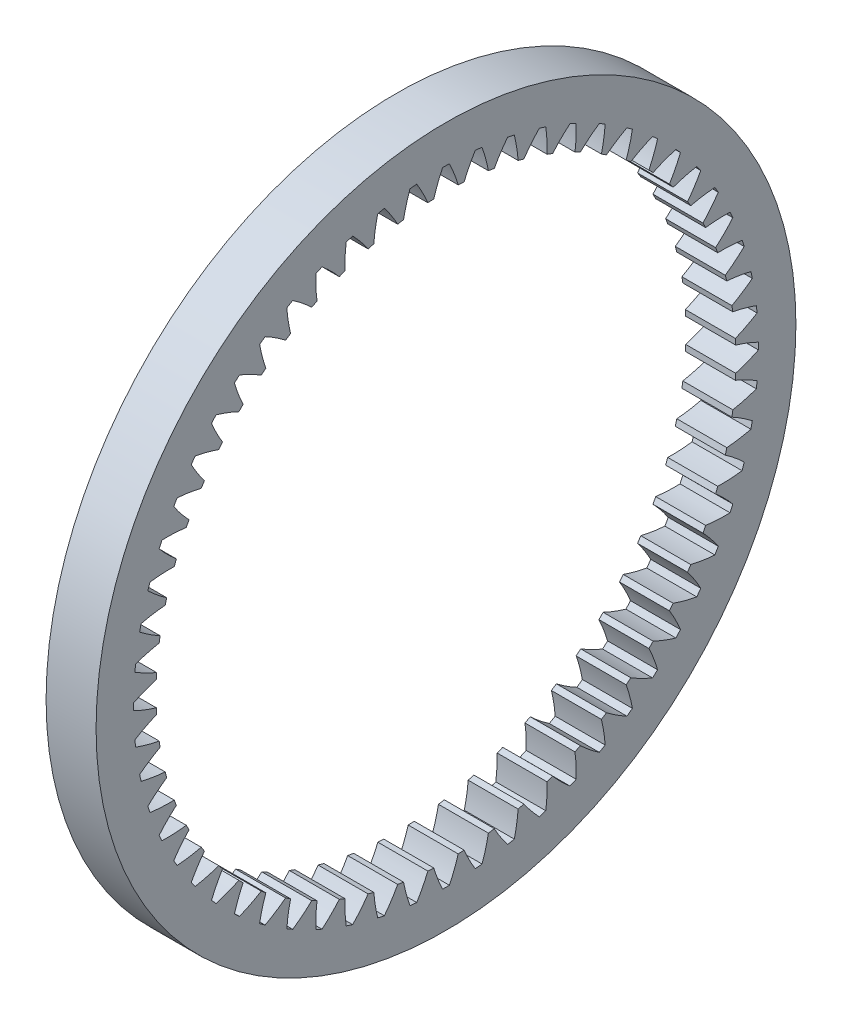
SolidWorks part; units mm, degrees
ref_plane "Plane1" through (0, 0, 0) normal (0, 0, 1) x (1, 0, 0)
ref_plane "Plane2" through (0, 0, 0) normal (0, 1, 0) x (1, 0, 0)
ref_plane "Plane3" through (0, 0, 0) normal (1, 0, 0) x (0, 0, -1)
sketch "HoldingSke" plane through (0, 0, 0) normal (0, 1, 0) x (1, 0, 0)
  line L0 (0, 0) -> (0.5, -0.866)
  line L1 (-15, 0) -> (100, 0) construction
  line L2 (0, 0) -> (-2.1039, 2.3779)
  line L3 (0, 0) -> (-11.863, 4.5341)
  line L4 (0, 0) -> (4.318, 7.479)
  line L5 (0, 0) -> (-23.7986, -8.8762)
  line L6 (0, 0) -> (-10.5278, -7.1032)
  line L7 (-2.1039, 2.3779) -> (3.3635, 27.1825)
  line L8 (-76.2, 3.3779) -> (-54.61, 3.3779)
  line L9 (-71.009, 38.7566) -> (-53.1078, 45.2721)
  line L10 (-76.2, 71.12) -> (104.1128, 71.12)
  line L11 (0, 0) -> (-5, 0)
  line L12 (-76.2, 101.6) -> (-76.162, 101.6)
  line L13 (24.9733, 27.94) -> (52.9518, 28.4284)
  line L14 (24.9733, 27.94) -> (24.9743, 27.94)
  line L15 (24.9733, 27.94) -> (100.4006, 29.5858)
  circle A0 centre (0, 0) radius 35
  circle A1 centre (0, 0) radius 12.7
  circle A2 centre (0, 0) radius 12.7
  dimension "MHD" = 25.4
  dimension "Hub_dia" = 25.4
  dimension "Diameter" = 70
  dimension "Num_teeth" = 60
  dimension "Pitch" = 1
  dimension "Overall_len" = 25.4
  dimension "Show_teeth" = 60
  dimension "Thickness" = 12.7
  dimension "OAL" = 25.4001
  dimension "T_dim" = 21.59
  dimension "Ap" = 20
  dimension "H" = 19.05
  dimension "Pitch_radius" = 180.3128
  dimension "Width" = 5
  dimension "Backlash" = 0.038
  dimension "Addendum_fac" = 1
  dimension "Dedendum_fac" = 1.25
  dimension "Clearance_fac" = 0.25
  dimension "Dedendum_add" = 0.001
  dimension "Module" = 1
sketch "BasProSke" plane through (0, 0, 0) normal (0, 1, 0) x (1, 0, 0)
  line L0 (-10, 0) -> (60, 0) construction
  line L1 (0, 29) -> (0, 35)
  line L2 (0, 29) -> (5, 29)
  line L3 (5, 29) -> (5, 35)
  line L4 (5, 35) -> (0, 35)
  dimension "Diameter" = 70
  dimension "Thickness" = 5
  dimension "Inside_diameter" = 58
revolve "Base-Revolve" add sketch "BasProSke" angle 360 about L0
sketch "TooCutSke" plane through (0, 0, 0) normal (1, 0, 0) x (0, 0, -1)
  line L3 (0.8803, 29.9871) -> (0.8803, 53.6633) construction
  line L4 (0, 0) -> (0, 59.563) construction
  line L5 (0, 0) -> (-3.576, 68.2339) construction
  line L6 (-13.1633, 24.7167) -> (36.4631, 27.3175) construction
  circle A0 centre (0, 0) radius 30 construction
  circle A1 centre (0, 0) radius 31.251 construction
  circle A2 centre (0, 0) radius 25.3717 construction
  circle A3 centre (0, 0) radius 28.9746 construction
  arc A4 (1.2274, 28.9486) -> (0.3395, 31.2492) centre (-13.1633, 24.7167) ccw
  arc A5 (1.2274, 28.9486) -> (-1.2274, 28.9486) centre (0, 0) ccw
  arc A6 (0.3395, 31.2492) -> (-0.3395, 31.2492) centre (0, 0) ccw
  arc A7 (-0.3395, 31.2492) -> (-1.2274, 28.9486) centre (13.1633, 24.7167) ccw
  dimension "Pitch_dia" = 60
  dimension "Base_dia" = 50.7434
  dimension "Root_dia" = 62.502
  dimension "Overcut_dia" = 57.9492
  dimension "Flank_rad" = 15
  dimension "Half_ang" = 3
  dimension "Half_CT" = 0.8803
extrude "ToothCut" cut sketch "TooCutSke" along normal through all
fillet "Breaks" [suppressed] radius 0.1
fillet "RootFillets" [suppressed] radius 0.251
pattern_circular "TeethCuts" count 60 every 6 about axis through (-10, 0, 0) along (1, 0, 0) of "RootFillets", "Breaks", "ToothCut"
equation "' \"Module@HoldingSke\" = 6.35"
equation "' \"Num_teeth@HoldingSke\" = 24"
equation "' \"Ap@HoldingSke\" =  14.5"
equation "' \"Ap@HoldingSke\" = 14.5"
equation "' \"Width@HoldingSke\" = 12"
equation "' \"Diameter@HoldingSke\" = 8 * 25.4"
equation "' \"Show_teeth@HoldingSke\" = 100"
equation "' \"Backlash@HoldingSke\" = 0.009 * 25.4"
equation "' \"Addendum_fac@HoldingSke\" = 1.0"
equation "' \"Dedendum_fac@HoldingSke\" = 1.25"
equation "' \"Dedendum_add@HoldingSke\" = 0.00005 * 25.4"
equation "' \"Clearance_fac@HoldingSke\" = 0.25"
equation "\"Pitch@HoldingSke\" = 1 / \"Module@HoldingSke\" "
equation "\"Overcut_dia@TooCutSke\" = (\"Num_teeth@HoldingSke\" - 2 * \"Addendum_fac@HoldingSke\") / \"Pitch@HoldingSke\" - 0.002 * 25.4"
equation "\"Pitch_dia@TooCutSke\" = \"Num_teeth@HoldingSke\" / \"Pitch@HoldingSke\""
equation "\"Base_dia@TooCutSke\" = \"Num_teeth@HoldingSke\" / \"Pitch@HoldingSke\" * cos((\"Ap@HoldingSke\"  * 3.14159265 / 180)) * 0.90"
equation "\"Root_dia@TooCutSke\" = \"Num_teeth@HoldingSke\"  / \"Pitch@HoldingSke\" + 2 *  \"Dedendum_fac@HoldingSke\"/ \"Pitch@HoldingSke\" + \"Dedendum_add@HoldingSke\" * 2"
equation "\"Half_ang@TooCutSke\" = 180 / \"Num_teeth@HoldingSke\""
equation "\"Half_CT@TooCutSke\" = \"Num_teeth@HoldingSke\" / \"Pitch@HoldingSke\" * sin((3.14159265 / 2 / \"Num_teeth@HoldingSke\")) / 2 + 10 * \"Backlash@HoldingSke\" / 4"
equation "\"Flank_rad@TooCutSke\" = \"Num_teeth@HoldingSke\" / \"Pitch@HoldingSke\" / 4"
equation "\"Radius@RootFillets\"= \"Clearance_fac@HoldingSke\" / \"Pitch@HoldingSke\" + \"Dedendum_add@HoldingSke\""
equation "\"Break_rad@Breaks\" = 0.02 / \"Pitch@HoldingSke\" * 5"
equation "\"Num_teeth@TeethCuts\" = int( \"Show_teeth@HoldingSke\" ) + 1"
equation "\"Num_teeth@TeethCuts\" = ((sgn( \"Num_teeth@TeethCuts\" - \"Num_teeth@HoldingSke\" )-1)*( \"Num_teeth@TeethCuts\" - \"Num_teeth@HoldingSke\" ))/-2+ \"Num_teeth@HoldingSke\""
equation "\"Num_teeth@TeethCuts\" = ((sgn( \"Num_teeth@TeethCuts\" - 2.0)+1)*( \"Num_teeth@TeethCuts\" - 2.0))/2 +2.0"
equation "\"Angle@TeethCuts\" = 360.0 / \"Num_teeth@HoldingSke\""
equation "\"Diameter@BasProSke\" = \"Num_teeth@HoldingSke\"  / \"Pitch@HoldingSke\" + 2 *  \"Dedendum_fac@HoldingSke\"/ \"Pitch@HoldingSke\" + \"Dedendum_add@HoldingSke\" * 2 + 0.002 * 25.4"
equation "\"Diameter@BasProSke\" = ((sgn( \"Diameter@BasProSke\"  - \"Diameter@HoldingSke\" )+1)*( \"Diameter@BasProSke\"  - \"Diameter@HoldingSke\" ))/2 + \"Diameter@HoldingSke\""
equation "\"Inside_diameter@BasProSke\" =  (\"Num_teeth@HoldingSke\" - 2 * \"Addendum_fac@HoldingSke\") / \"Pitch@HoldingSke\" "
equation "\"Thickness@BasProSke\"  = \"Width@HoldingSke\""
